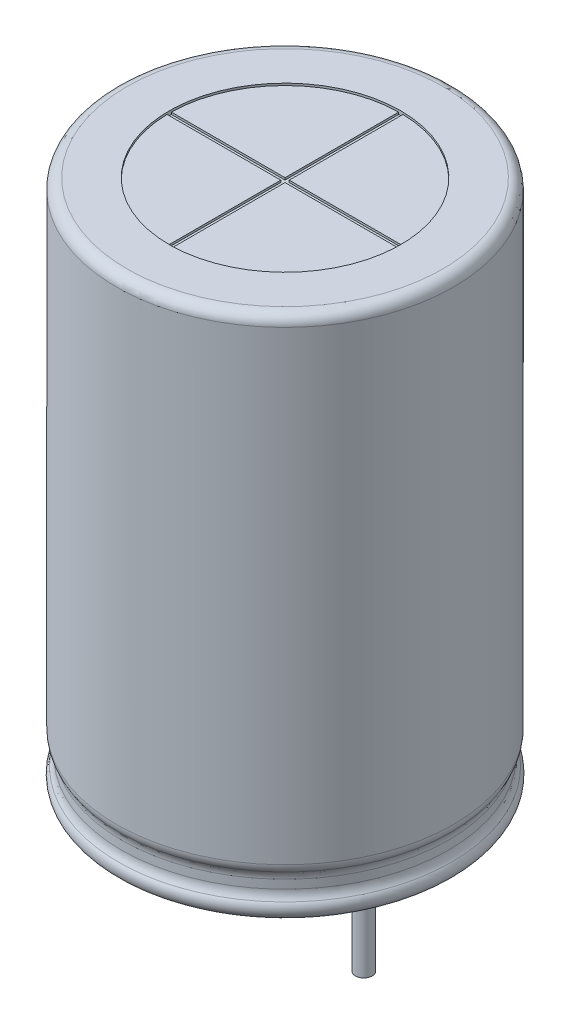
SolidWorks part; units mm, degrees
ref_plane "Front Plane" through (0, 0, 0) normal (0, 0, 1) x (1, 0, 0)
ref_plane "Top Plane" through (0, 0, 0) normal (0, 1, 0) x (1, 0, 0)
ref_plane "Right Plane" through (0, 0, 0) normal (1, 0, 0) x (0, 0, -1)
sketch "Sketch1" plane through (0, 0, 0) normal (0, 0, 1) x (1, 0, 0)
  line L0 (8, 25) -> (0, 25)
  line L1 (0, 25) -> (0, 0)
  line L2 (0, 0) -> (8, 0)
  line L3 (7.7604, 1.2326) -> (7.7604, 1.6424)
  line L4 (8, 2.4076) -> (8, 25)
  line L5 (0, 25) -> (0, 0) construction
  arc A0 (8, 0) -> (7.9281, 0.789) centre (7.4249, 0.3453) ccw
  arc A1 (7.9281, 0.789) -> (7.7604, 1.2326) centre (8.4312, 1.2326) cw
  arc A2 (7.7604, 1.6424) -> (7.8802, 2.025) centre (8.4312, 1.6424) cw
  arc A3 (7.8802, 2.025) -> (8, 2.4076) centre (7.3292, 2.4076) ccw
  dimension "D1" = 25
  dimension "D2" = 8
revolve "Revolve1" add sketch "Sketch1" angle 360 about L5
sketch "Sketch2" plane through (0, 25, 0) normal (0, 1, 0) x (-1, 0, 0)
  circle A0 centre (0, 0) radius 5.5
  dimension "D1" = 11
extrude "Cut-Extrude1" cut sketch "Sketch2" against normal blind 0.1
sketch "Sketch3" plane through (0, 24.9, 0) normal (0, 1, 0) x (-1, 0, 0)
  line L0 (-5.4991, -0.1) -> (-0.1, -0.1)
  line L1 (-0.1, -0.1) -> (-0.1, -5.4991)
  line L2 (-0.1, 5.4991) -> (-0.1, 0.1)
  line L3 (-0.1, 0.1) -> (-5.4991, 0.1)
  line L4 (5.4991, 0.1) -> (0.1, 0.1)
  line L5 (0.1, 0.1) -> (0.1, 5.4991)
  line L6 (0.1, -5.4991) -> (0.1, -0.1)
  line L7 (0.1, -0.1) -> (5.4991, -0.1)
  line L9 (0, 6.2081) -> (0, -6.5499) construction
  line L10 (6.8771, 0) -> (-11.2847, 0) construction
  circle A0 centre (0, 0) radius 5.5 construction
  arc A1 (-5.5, 0) -> (-5.4991, -0.1) centre (0, 0) ccw
  arc A2 (-0.1, -5.4991) -> (0, -5.5) centre (0, 0) ccw
  arc A3 (0, 5.5) -> (-0.1, 5.4991) centre (0, 0) ccw
  arc A4 (-5.4991, 0.1) -> (-5.5, 0) centre (0, 0) ccw
  arc A5 (5.5, 0) -> (5.4991, 0.1) centre (0, 0) ccw
  arc A6 (0.1, 5.4991) -> (0, 5.5) centre (0, 0) ccw
  arc A7 (0, -5.5) -> (0.1, -5.4991) centre (0, 0) ccw
  arc A8 (5.4991, -0.1) -> (5.5, 0) centre (0, 0) ccw
  dimension "D1" = 0.1
  dimension "D2" = 0.1
  dimension "D3" = 4
extrude "Cut-Extrude2" cut sketch "Sketch3" against normal blind 0.1
ref_plane "Plane1" through (0, 0, 0) normal (0, 0, -1) x (-1, 0, 0)
sketch "Croquis1" plane through (0, 0, 0) normal (0, -1, 0) x (1, 0, 0)
  circle A0 centre (0, 0) radius 5.5
  dimension "D1" = 11
extrude "Cortar-Extruir1" cut sketch "Croquis1" against normal blind 0.25
sketch "Sketch4" plane through (0, 0, 0) normal (0, 0, -1) x (-1, 0, 0)
  line L0 (-4.1417, -5.75) -> (-3.7417, -5.75)
  line L1 (-3.7417, -5.75) -> (-3.7417, 0.25)
  line L2 (-3.7417, 0.25) -> (-4.1417, 0.25)
  line L3 (-4.1417, 0.25) -> (-4.1417, -5.75)
  line L4 (-3.7417, -5.75) -> (-3.7417, 0.25) construction
  line L9 (-5.5, 0.25) -> (5.5, 0.25) construction
  dimension "D1" = 3.75
  dimension "D2" = 0.4
  dimension "D3" = 6
fillet "Fillet1" radius 0.5 2 edges at (8, 25, 0) (8, 0, 0)
revolve "Revolución1" add sketch "Sketch4" angle 360 about L4
mirror "Simetría1" about plane through (0, 0, 0) normal (1, 0, 0) of "Revolución1"
